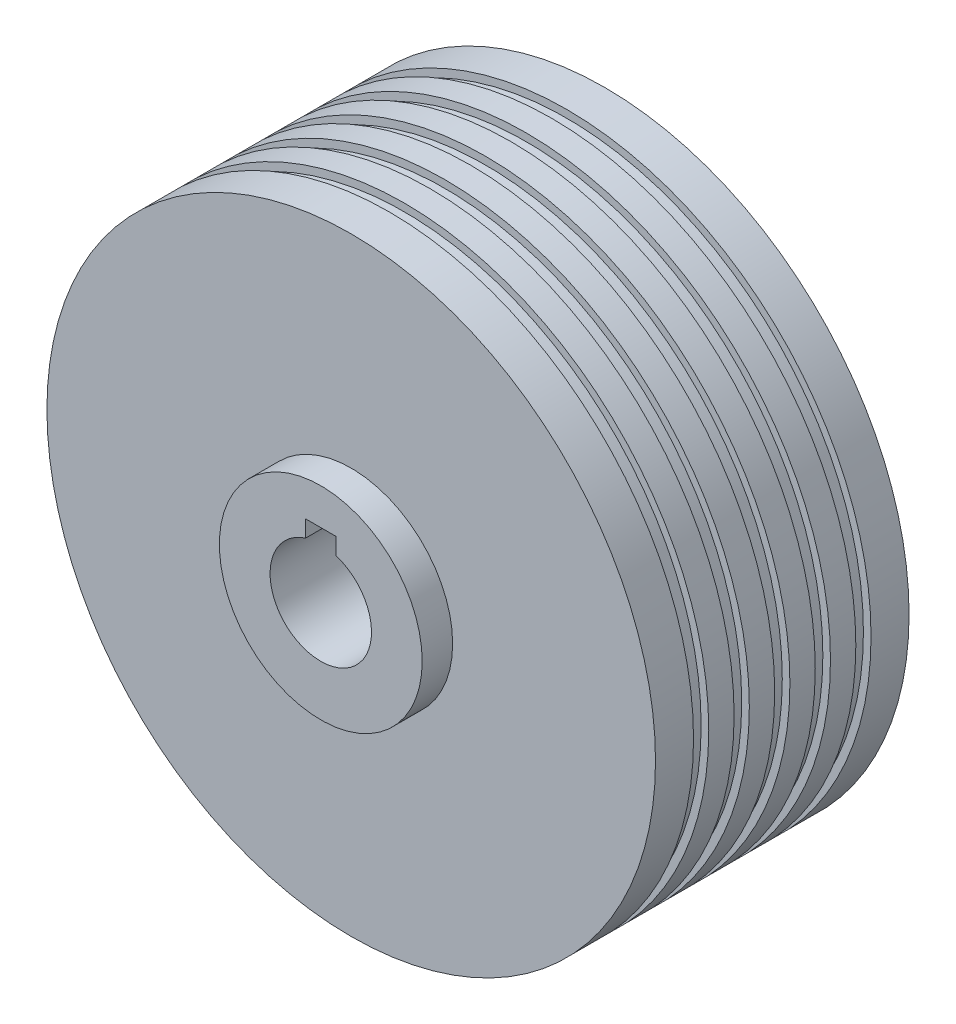
SolidWorks part; units mm, degrees
material "Nylon 101"
ref_plane "Front Plane" through (0, 0, 0) normal (0, 0, 1) x (1, 0, 0)
ref_plane "Top Plane" through (0, 0, 0) normal (0, 1, 0) x (1, 0, 0)
ref_plane "Right Plane" through (0, 0, 0) normal (1, 0, 0) x (0, 0, -1)
sketch "Sketch1" plane through (0, 0, 0) normal (0, 0, 1) x (1, 0, 0)
  circle A0 centre (0, 0) radius 30
  dimension "D1" = 60
extrude "Boss-Extrude1" add sketch "Sketch1" along normal blind 25
sketch "Sketch2" plane through (0, 0, 25) normal (0, 0, 1) x (1, 0, 0)
  circle A0 centre (0, 0) radius 5
  dimension "D1" = 10
extrude "Cut-Extrude1" cut sketch "Sketch2" against normal blind 43 and the other way blind 1
sketch "Sketch3" plane through (0, 0, 0) normal (1, 0, 0) x (0, 0, -1)
  line L0 (0, 30) -> (-25, 30) construction
  line L1 (-13.25, 30.75) -> (-11.75, 30.75)
  line L2 (-13.25, 30.75) -> (-13.25, 29.25)
  line L3 (-13.25, 29.25) -> (-11.75, 29.25)
  line L4 (-11.75, 30.75) -> (-11.75, 29.25)
  line L5 (-13.25, 30.75) -> (-11.75, 29.25) construction
  line L6 (-13.25, 29.25) -> (-11.75, 30.75) construction
  line L7 (-9.25, 30.75) -> (-9.25, 29.25)
  line L8 (-9.25, 30.75) -> (-7.75, 30.75)
  line L9 (-7.75, 30.75) -> (-7.75, 29.25)
  line L10 (-9.25, 29.25) -> (-7.75, 29.25)
  line L11 (-5.25, 30.75) -> (-5.25, 29.25)
  line L12 (-5.25, 30.75) -> (-3.75, 30.75)
  line L13 (-3.75, 30.75) -> (-3.75, 29.25)
  line L14 (-5.25, 29.25) -> (-3.75, 29.25)
  line L15 (-17.25, 30.75) -> (-17.25, 29.25)
  line L16 (-17.25, 30.75) -> (-15.75, 30.75)
  line L17 (-15.75, 30.75) -> (-15.75, 29.25)
  line L18 (-17.25, 29.25) -> (-15.75, 29.25)
  line L19 (-21.25, 30.75) -> (-21.25, 29.25)
  line L20 (-21.25, 30.75) -> (-19.75, 30.75)
  line L21 (-19.75, 30.75) -> (-19.75, 29.25)
  line L22 (-21.25, 29.25) -> (-19.75, 29.25)
  point P0 (-12.5, 30)
  dimension "D1" = 1.5
  dimension "D2" = 1.5
  dimension "D3" = 3
  dimension "D4" = 3
revolve "Cut-Revolve2" cut sketch "Sketch3" angle 360 about axis through (0, 0, 25) along (0, 0, -1)
sketch "Sketch5" plane through (0, 0, 25) normal (0, 0, 1) x (1, 0, 0)
  circle A1 centre (0, 0) radius 10
  dimension "D1" = 20
extrude "Boss-Extrude2" add sketch "Sketch5" along normal blind 3
sketch "Sketch6" plane through (0, 0, 28) normal (0, 0, 1) x (1, 0, 0)
  circle A0 centre (0, 0) radius 5
  dimension "D1" = 10
extrude "Cut-Extrude3" cut sketch "Sketch6" against normal blind 3
sketch "Sketch7" plane through (0, 0, 0) normal (0, 0, -1) x (-1, 0, 0)
  line L0 (-1.5, 6.4197) -> (1.5, 6.4197)
  line L9 (-1.5, 6.4197) -> (-1.5, 4.7697)
  line L10 (1.5, 6.4197) -> (1.5, 4.7697)
  circle A2 centre (0, 0) radius 5 construction
  arc A3 (-1.5, 4.7697) -> (1.5, 4.7697) centre (0, 0) cw
  point P3 (0, 6.4197)
  dimension "D1" = 3
  dimension "D2" = 0
  dimension "D3" = 1.65
extrude "Cut-Extrude4" cut sketch "Sketch7" against normal blind 38
